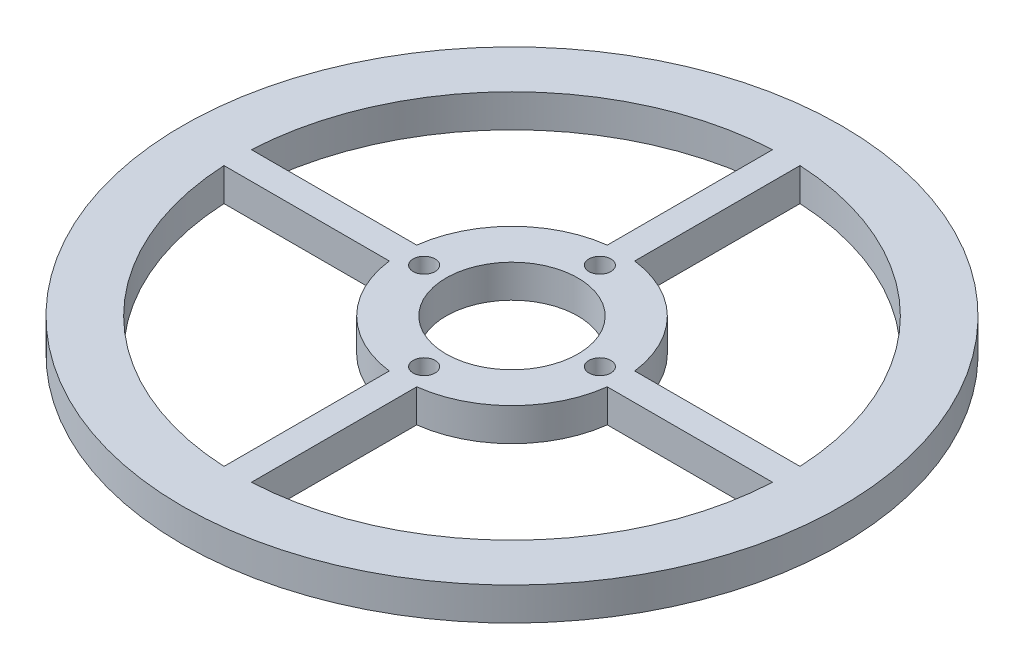
SolidWorks part; units mm, degrees
ref_plane "前视基准面" through (0, 0, 0) normal (0, 0, 1) x (1, 0, 0)
ref_plane "上视基准面" through (0, 0, 0) normal (0, 1, 0) x (1, 0, 0)
ref_plane "右视基准面" through (0, 0, 0) normal (1, 0, 0) x (0, 0, -1)
other "Configuration Table"
sketch "草图1" plane through (0, 0, 0) normal (0, 1, 0) x (1, 0, 0)
  line L0 (0, 0) -> (8, 0) construction
  line L1 (0, 0) -> (0, 8) construction
  line L2 (9.9216, 1.25) -> (24.9687, 1.25)
  line L3 (9.9216, -1.25) -> (24.9687, -1.25)
  line L4 (1.25, -9.9216) -> (1.25, -24.9687)
  line L5 (-1.25, -9.9216) -> (-1.25, -24.9687)
  line L6 (-9.9216, -1.25) -> (-24.9687, -1.25)
  line L7 (-9.9216, 1.25) -> (-24.9687, 1.25)
  line L8 (-1.25, 9.9216) -> (-1.25, 24.9687)
  line L9 (1.25, 9.9216) -> (1.25, 24.9687)
  circle A0 centre (0, 0) radius 30
  circle A1 centre (0, 0) radius 8 construction
  circle A2 centre (8, 0) radius 1
  circle A3 centre (0, -8) radius 1
  circle A4 centre (-8, 0) radius 1
  circle A5 centre (0, 8) radius 1
  circle A6 centre (0, 0) radius 6
  circle A7 centre (0, 0) radius 10
  circle A8 centre (0, 0) radius 25
  dimension "D1" = 60
  dimension "D2" = 16
  dimension "D3" = 2
  dimension "D5" = 12
  dimension "D6" = 20
  dimension "D7" = 50
  dimension "D8" = 2.5
  dimension "D4" = 4
  dimension "D9" = 4
extrude "凸台-拉伸1" add sketch "草图1" along normal blind 3
